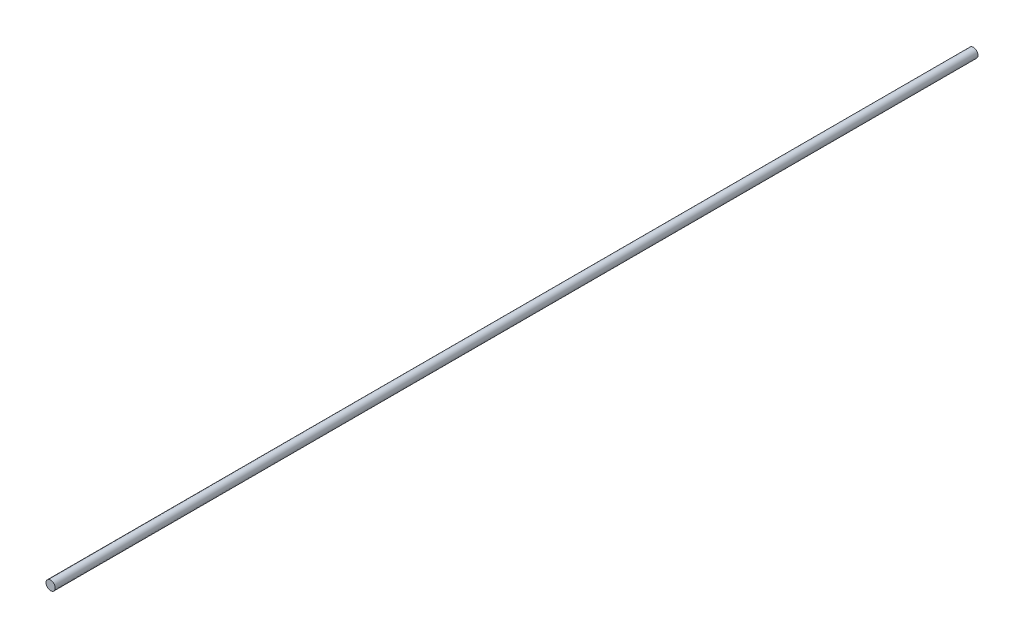
SolidWorks part; units mm, degrees
ref_plane "前视基准面" through (0, 0, 0) normal (0, 0, 1) x (1, 0, 0)
ref_plane "上视基准面" through (0, 0, 0) normal (0, 1, 0) x (1, 0, 0)
ref_plane "右视基准面" through (0, 0, 0) normal (1, 0, 0) x (0, 0, -1)
sketch "草图1" plane through (0, 0, 0) normal (0, 0, 1) x (1, 0, 0)
  circle A0 centre (0, 0) radius 0.75
  dimension "D1" = 1.5
extrude "凸台-拉伸1" add sketch "草图1" along normal blind 150
